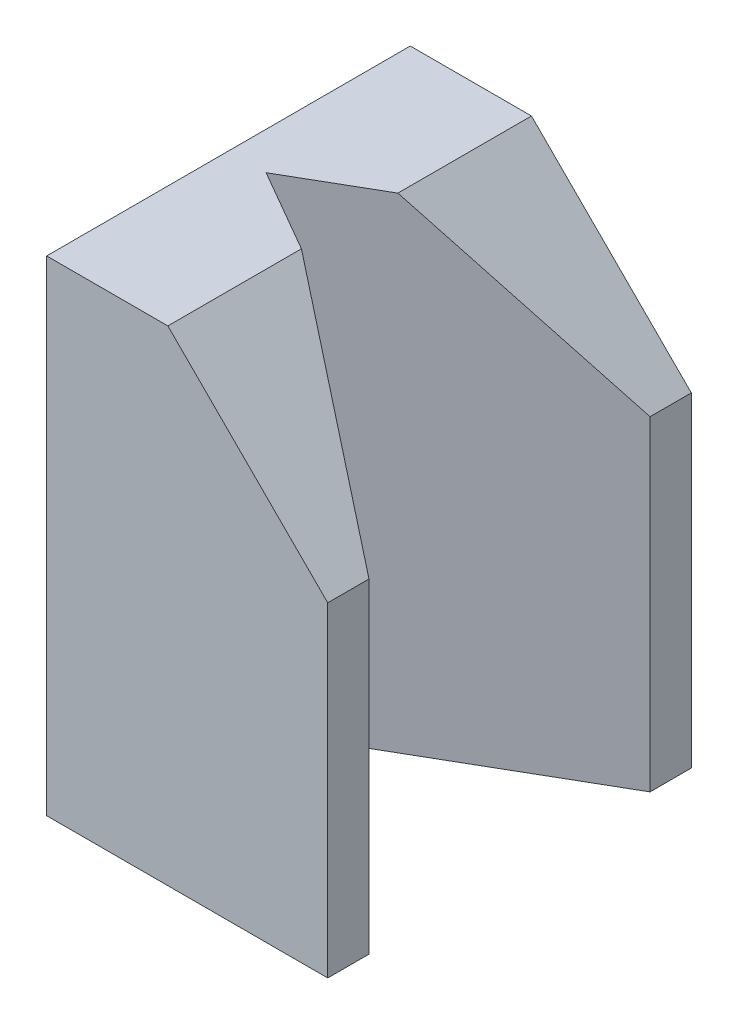
SolidWorks part; units mm, degrees
ref_plane "Front Plane" through (0, 0, 0) normal (0, 0, 1) x (1, 0, 0)
ref_plane "Top Plane" through (0, 0, 0) normal (0, 1, 0) x (1, 0, 0)
ref_plane "Right Plane" through (0, 0, 0) normal (1, 0, 0) x (0, 0, -1)
sketch "Sketch1" plane through (0, 0, 0) normal (0, 1, 0) x (1, 0, 0)
  line L0 (44.1775, 22.3216) -> (0, 22.3216)
  line L1 (0, 22.3216) -> (0, -34.8284)
  line L2 (0, -34.8284) -> (44.1775, -34.8284)
  line L3 (44.1775, -34.8284) -> (44.1775, -28.3422)
  line L4 (44.1775, -28.3422) -> (5.9187, -6.2534)
  line L5 (5.9187, -6.2534) -> (44.1775, 15.8353)
  line L6 (44.1775, 15.8353) -> (44.1775, 22.3216)
  line L7 (5.9187, -6.2534) -> (44.1775, -6.2534) construction
  line L8 (44.1775, 15.8353) -> (44.1775, -6.2534) construction
  dimension "D1" = 57.15
  dimension "D2" = 44.1775
  dimension "D3" = 30
  dimension "D4" = 30
extrude "Boss-Extrude1" add sketch "Sketch1" along normal blind 76.2
sketch "Sketch3" plane through (0, 0, 0) normal (0, 0, 1) x (1, 0, 0)
  line L0 (19.05, 76.2) -> (19.05, 0) construction
  line L1 (0, 76.2) -> (44.1775, 76.2) construction
  line L2 (0, 0) -> (44.1775, 0) construction
  line L3 (0, 76.2) -> (0, 0) construction
  line L4 (19.05, 76.2) -> (44.1775, 51.0725)
  line L5 (44.1775, 76.2) -> (44.1775, 0) construction
  dimension "D1" = 19.05
  dimension "D2" = 45
extrude "Cut-Extrude1" cut sketch "Sketch3" against normal through all and the other way through all
